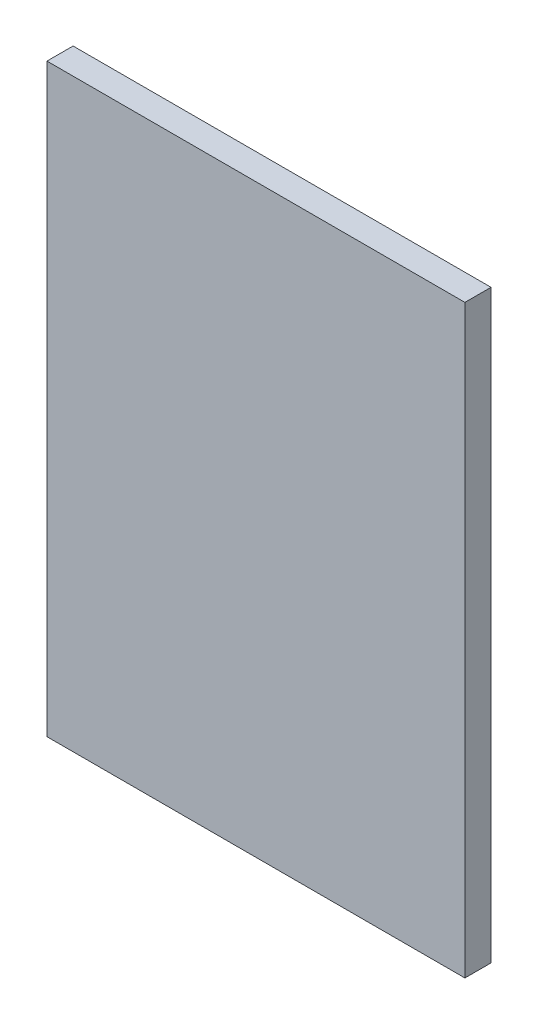
SolidWorks part; units mm, degrees
ref_plane "Front Plane" through (0, 0, 0) normal (0, 0, 1) x (1, 0, 0)
ref_plane "Top Plane" through (0, 0, 0) normal (0, 1, 0) x (1, 0, 0)
ref_plane "Right Plane" through (0, 0, 0) normal (1, 0, 0) x (0, 0, -1)
sketch "Sketch1" plane through (0, 0, 0) normal (0, 0, 1) x (1, 0, 0)
  line L1 (25.4, -35.56) -> (-25.4, -35.56)
  line L2 (25.4, -35.56) -> (25.4, 35.56)
  line L3 (25.4, 35.56) -> (-25.4, 35.56)
  line L4 (-25.4, -35.56) -> (-25.4, 35.56)
  line L5 (25.4, -35.56) -> (-25.4, 35.56) construction
  line L6 (25.4, 35.56) -> (-25.4, -35.56) construction
  point P0 (0, 0)
  dimension "D1" = 71.12
  dimension "D2" = 50.8
extrude "Boss-Extrude1" add sketch "Sketch1" along normal blind 3.175
